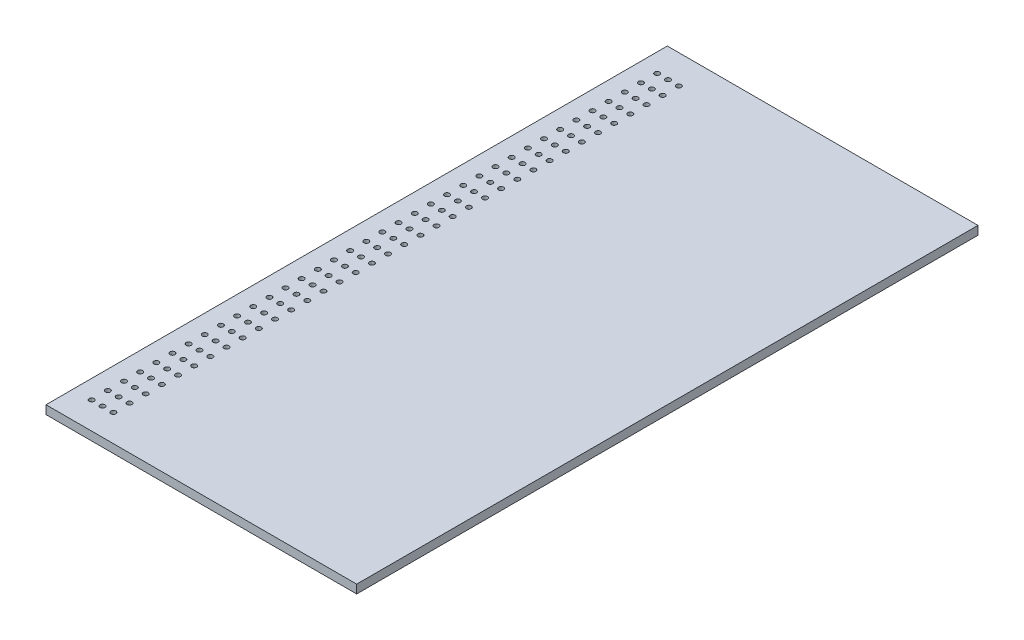
SolidWorks part; units mm, degrees
ref_plane "Front Plane" through (0, 0, 0) normal (0, 0, 1) x (1, 0, 0)
ref_plane "Top Plane" through (0, 0, 0) normal (0, 1, 0) x (1, 0, 0)
ref_plane "Right Plane" through (0, 0, 0) normal (1, 0, 0) x (0, 0, -1)
sketch "Sketch1" plane through (0, 0, 0) normal (0, 1, 0) x (1, 0, 0)
  line L1 (0, 0) -> (50, 0)
  line L2 (0, 0) -> (0, -100)
  line L3 (0, -100) -> (50, -100)
  line L4 (50, 0) -> (50, -100)
  dimension "D1" = 50
  dimension "D2" = 100
extrude "Boss-Extrude1" add sketch "Sketch1" along normal blind 1.38
sketch "Sketch2" plane through (0, 1.38, 0) normal (0, 1, 0) x (1, 0, 0)
  line L0 (50, 0) -> (0, 0) construction
  line L1 (0, 0) -> (0, -100) construction
  circle A0 centre (3, -4.65) radius 0.4
  circle A1 centre (4.75, -4.65) radius 0.4
  circle A2 centre (6.5, -4.65) radius 0.4
  circle A3 centre (3, -7.25) radius 0.4
  circle A4 centre (4.75, -7.25) radius 0.4
  circle A5 centre (6.5, -7.25) radius 0.4
  circle A6 centre (3, -9.85) radius 0.4
  circle A7 centre (4.75, -9.85) radius 0.4
  circle A8 centre (6.5, -9.85) radius 0.4
  circle A9 centre (3, -12.45) radius 0.4
  circle A10 centre (4.75, -12.45) radius 0.4
  circle A11 centre (6.5, -12.45) radius 0.4
  circle A12 centre (3, -15.05) radius 0.4
  circle A13 centre (4.75, -15.05) radius 0.4
  circle A14 centre (6.5, -15.05) radius 0.4
  circle A15 centre (3, -17.65) radius 0.4
  circle A16 centre (4.75, -17.65) radius 0.4
  circle A17 centre (6.5, -17.65) radius 0.4
  circle A18 centre (3, -20.25) radius 0.4
  circle A19 centre (4.75, -20.25) radius 0.4
  circle A20 centre (6.5, -20.25) radius 0.4
  circle A21 centre (3, -22.85) radius 0.4
  circle A22 centre (4.75, -22.85) radius 0.4
  circle A23 centre (6.5, -22.85) radius 0.4
  circle A24 centre (3, -25.45) radius 0.4
  circle A25 centre (4.75, -25.45) radius 0.4
  circle A26 centre (6.5, -25.45) radius 0.4
  circle A27 centre (3, -28.05) radius 0.4
  circle A28 centre (4.75, -28.05) radius 0.4
  circle A29 centre (6.5, -28.05) radius 0.4
  circle A30 centre (3, -30.65) radius 0.4
  circle A31 centre (4.75, -30.65) radius 0.4
  circle A32 centre (6.5, -30.65) radius 0.4
  circle A33 centre (3, -33.25) radius 0.4
  circle A34 centre (4.75, -33.25) radius 0.4
  circle A35 centre (6.5, -33.25) radius 0.4
  circle A36 centre (3, -35.85) radius 0.4
  circle A37 centre (4.75, -35.85) radius 0.4
  circle A38 centre (6.5, -35.85) radius 0.4
  circle A39 centre (3, -38.45) radius 0.4
  circle A40 centre (4.75, -38.45) radius 0.4
  circle A41 centre (6.5, -38.45) radius 0.4
  circle A42 centre (3, -41.05) radius 0.4
  circle A43 centre (4.75, -41.05) radius 0.4
  circle A44 centre (6.5, -41.05) radius 0.4
  circle A45 centre (3, -43.65) radius 0.4
  circle A46 centre (4.75, -43.65) radius 0.4
  circle A47 centre (6.5, -43.65) radius 0.4
  circle A48 centre (3, -46.25) radius 0.4
  circle A49 centre (4.75, -46.25) radius 0.4
  circle A50 centre (6.5, -46.25) radius 0.4
  circle A51 centre (3, -48.85) radius 0.4
  circle A52 centre (4.75, -48.85) radius 0.4
  circle A53 centre (6.5, -48.85) radius 0.4
  circle A54 centre (3, -51.45) radius 0.4
  circle A55 centre (4.75, -51.45) radius 0.4
  circle A56 centre (6.5, -51.45) radius 0.4
  circle A57 centre (3, -54.05) radius 0.4
  circle A58 centre (4.75, -54.05) radius 0.4
  circle A59 centre (6.5, -54.05) radius 0.4
  circle A60 centre (3, -56.65) radius 0.4
  circle A61 centre (4.75, -56.65) radius 0.4
  circle A62 centre (6.5, -56.65) radius 0.4
  circle A63 centre (3, -59.25) radius 0.4
  circle A64 centre (4.75, -59.25) radius 0.4
  circle A65 centre (6.5, -59.25) radius 0.4
  circle A66 centre (3, -61.85) radius 0.4
  circle A67 centre (4.75, -61.85) radius 0.4
  circle A68 centre (6.5, -61.85) radius 0.4
  circle A69 centre (3, -64.45) radius 0.4
  circle A70 centre (4.75, -64.45) radius 0.4
  circle A71 centre (6.5, -64.45) radius 0.4
  circle A72 centre (3, -67.05) radius 0.4
  circle A73 centre (4.75, -67.05) radius 0.4
  circle A74 centre (6.5, -67.05) radius 0.4
  circle A75 centre (3, -69.65) radius 0.4
  circle A76 centre (4.75, -69.65) radius 0.4
  circle A77 centre (6.5, -69.65) radius 0.4
  circle A78 centre (3, -72.25) radius 0.4
  circle A79 centre (4.75, -72.25) radius 0.4
  circle A80 centre (6.5, -72.25) radius 0.4
  circle A81 centre (3, -74.85) radius 0.4
  circle A82 centre (4.75, -74.85) radius 0.4
  circle A83 centre (6.5, -74.85) radius 0.4
  circle A84 centre (3, -77.45) radius 0.4
  circle A85 centre (4.75, -77.45) radius 0.4
  circle A86 centre (6.5, -77.45) radius 0.4
  circle A87 centre (3, -80.05) radius 0.4
  circle A88 centre (4.75, -80.05) radius 0.4
  circle A89 centre (6.5, -80.05) radius 0.4
  circle A90 centre (3, -82.65) radius 0.4
  circle A91 centre (4.75, -82.65) radius 0.4
  circle A92 centre (6.5, -82.65) radius 0.4
  circle A93 centre (3, -85.25) radius 0.4
  circle A94 centre (4.75, -85.25) radius 0.4
  circle A95 centre (6.5, -85.25) radius 0.4
  circle A96 centre (3, -87.85) radius 0.4
  circle A97 centre (4.75, -87.85) radius 0.4
  circle A98 centre (6.5, -87.85) radius 0.4
  circle A99 centre (3, -90.45) radius 0.4
  circle A100 centre (4.75, -90.45) radius 0.4
  circle A101 centre (6.5, -90.45) radius 0.4
  circle A102 centre (3, -93.05) radius 0.4
  circle A103 centre (4.75, -93.05) radius 0.4
  circle A104 centre (6.5, -93.05) radius 0.4
  circle A105 centre (3, -95.65) radius 0.4
  circle A106 centre (4.75, -95.65) radius 0.4
  circle A107 centre (6.5, -95.65) radius 0.4
  dimension "D1" = 4.65
  dimension "D2" = 0.8
  dimension "D3" = 3
  dimension "D6" = 2.6
  dimension "D4" = 3
  dimension "D5" = 36
extrude "Cut-Extrude1" cut sketch "Sketch2" against normal blind 1.38
